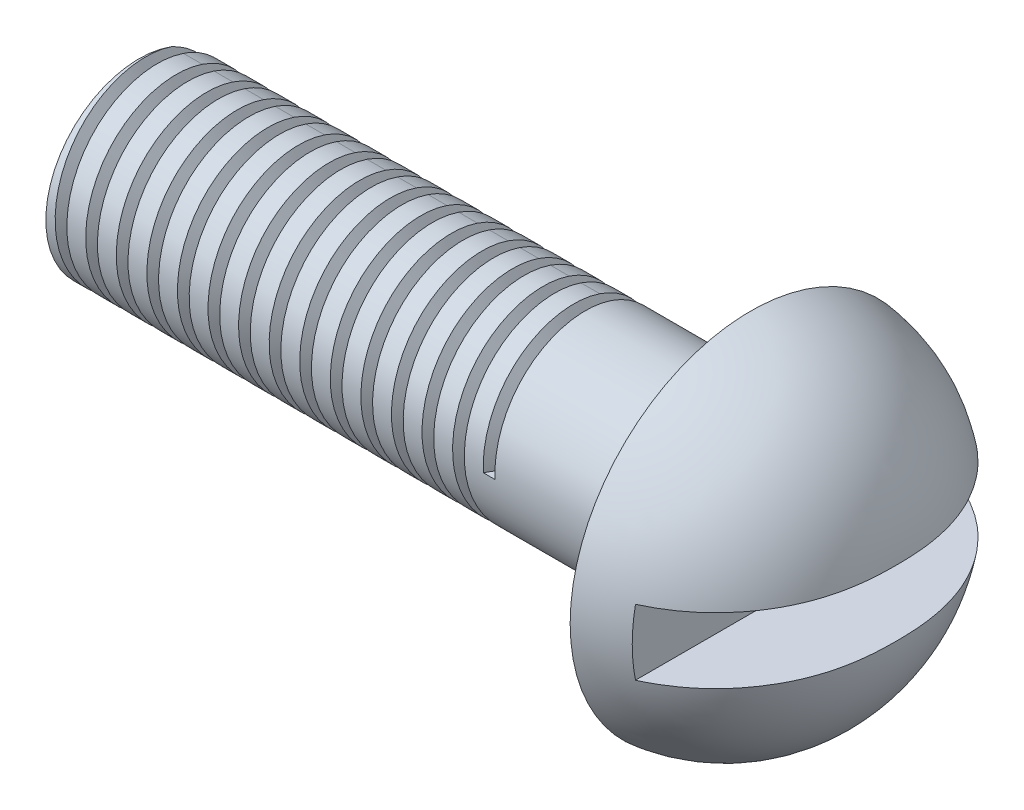
SolidWorks part; units mm, degrees
material "1.7030 (28Cr4)"
ref_plane "Alzado" through (0, 0, 0) normal (0, 0, 1) x (1, 0, 0)
ref_plane "Planta" through (0, 0, 0) normal (0, 1, 0) x (1, 0, 0)
ref_plane "Vista lateral" through (0, 0, 0) normal (1, 0, 0) x (0, 0, -1)
sketch "Croquis1" plane through (0, 0, 0) normal (0, 0, 1) x (1, 0, 0)
  line L0 (0, 0) -> (0.95, 0)
  line L1 (0, 0) -> (0, 1.18)
  arc A0 (0, 1.18) -> (0.95, 0) centre (-0.115, 0.115) cw
revolve "Revolución1" add sketch "Croquis1" angle 360 about L0
sketch "Croquis2" plane through (0, 0, 0) normal (0, 0, 1) x (1, 0, 0)
  line L1 (0.32, -0.215) -> (1.58, -0.215)
  line L2 (0.32, -0.215) -> (0.32, 0.215)
  line L3 (0.32, 0.215) -> (1.58, 0.215)
  line L4 (1.58, -0.215) -> (1.58, 0.215)
  line L5 (0.32, -0.215) -> (1.58, 0.215) construction
  line L6 (0.32, 0.215) -> (1.58, -0.215) construction
  point P0 (0.95, 0)
  point P6 (0.95, 0.215)
  dimension "D1" = 0.43
  dimension "D2" = 0.63
extrude "Cortar-Extruir1" cut sketch "Croquis2" against normal mid plane 3
sketch "Croquis3" plane through (0, 0, 0) normal (-1, 0, 0) x (0, 0, 1)
  circle A0 centre (0, 0) radius 0.61
extrude "Saliente-Extruir1" add sketch "Croquis3" along normal blind 4
sketch "Croquis4" plane through (-4, 0, 0) normal (-1, 0, 0) x (0, 0, 1)
  circle A0 centre (0, 0) radius 0.61
curve "Hélice/Espiral1" pitch 0.2 height 3 turns 15
sketch "Croquis5" plane through (0, 0, 0) normal (0, 1, 0) x (1, 0, 0)
  line L1 (-4, 0.5437) -> (-3.9425, 0.6432)
  line L2 (-3.9425, 0.6432) -> (-4.0575, 0.6432)
  line L3 (-4.0575, 0.6432) -> (-4, 0.5437)
  circle A0 centre (-4, 0.61) radius 0.0332 construction
sweep "Cortar-Barrer1" cut profiles "Croquis5" path "Hélice/Espiral1"
